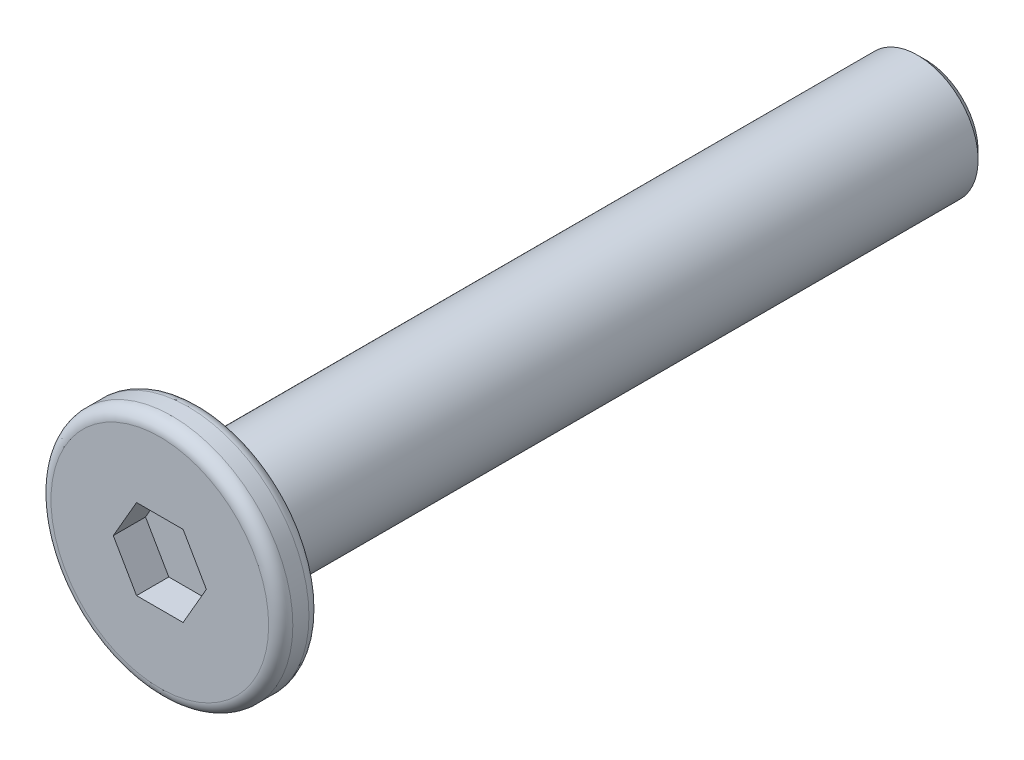
SolidWorks part; units mm, degrees
ref_plane "前视基准面" through (0, 0, 0) normal (0, 0, 1) x (1, 0, 0)
ref_plane "上视基准面" through (0, 0, 0) normal (0, 1, 0) x (1, 0, 0)
ref_plane "右视基准面" through (0, 0, 0) normal (1, 0, 0) x (0, 0, -1)
sketch "草图1" plane through (0, 0, 0) normal (0, 0, 1) x (1, 0, 0)
  circle A0 centre (0, 0) radius 3
  dimension "D1" = 6
extrude "凸台-拉伸1" add sketch "草图1" along normal mid plane 1
sketch "草图2" plane through (0, 0, -0.5) normal (0, 0, -1) x (-1, 0, 0)
  circle A0 centre (0, 0) radius 1.5
  dimension "D1" = 3
extrude "凸台-拉伸2" add sketch "草图2" along normal blind 18
chamfer "倒角1" distance 0.2 angle 45 1 edges at (-1.5, 0, -18.5)
sketch "草图3" plane through (0, 0, 0.5) normal (0, 0, 1) x (1, 0, 0)
  line L1 (1.1547, 0) -> (0.5774, 1)
  line L2 (0.5774, 1) -> (-0.5774, 1)
  line L3 (-0.5774, 1) -> (-1.1547, 0)
  line L4 (-1.1547, 0) -> (-0.5774, -1)
  line L5 (-0.5774, -1) -> (0.5774, -1)
  line L6 (0.5774, -1) -> (1.1547, 0)
  circle A0 centre (0, 0) radius 1 construction
  dimension "D1" = 2
extrude "切除-拉伸1" cut sketch "草图3" against normal blind 0.8
fillet "圆角2" radius 0.3 2 edges at (3, 0, -0.5) (3, 0, 0.5)
